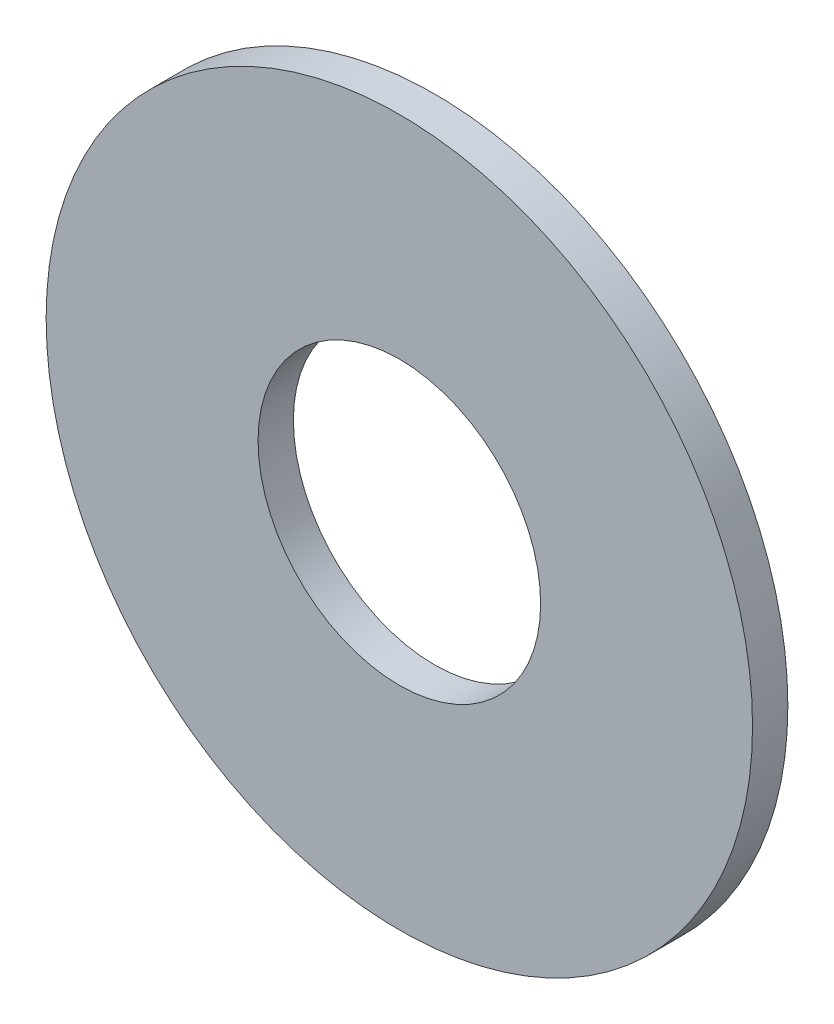
SolidWorks part; units mm, degrees
ref_plane "Front Plane" through (0, 0, 0) normal (0, 0, 1) x (1, 0, 0)
ref_plane "Top Plane" through (0, 0, 0) normal (0, 1, 0) x (1, 0, 0)
ref_plane "Right Plane" through (0, 0, 0) normal (1, 0, 0) x (0, 0, -1)
sketch "Sketch1" plane through (0, 0, 0) normal (0, 0, 1) x (1, 0, 0)
  circle A0 centre (0, 0) radius 4
  circle A1 centre (0, 0) radius 10
  dimension "D1" = 8
  dimension "D2" = 20
extrude "Boss-Extrude1" add sketch "Sketch1" along normal blind 1
